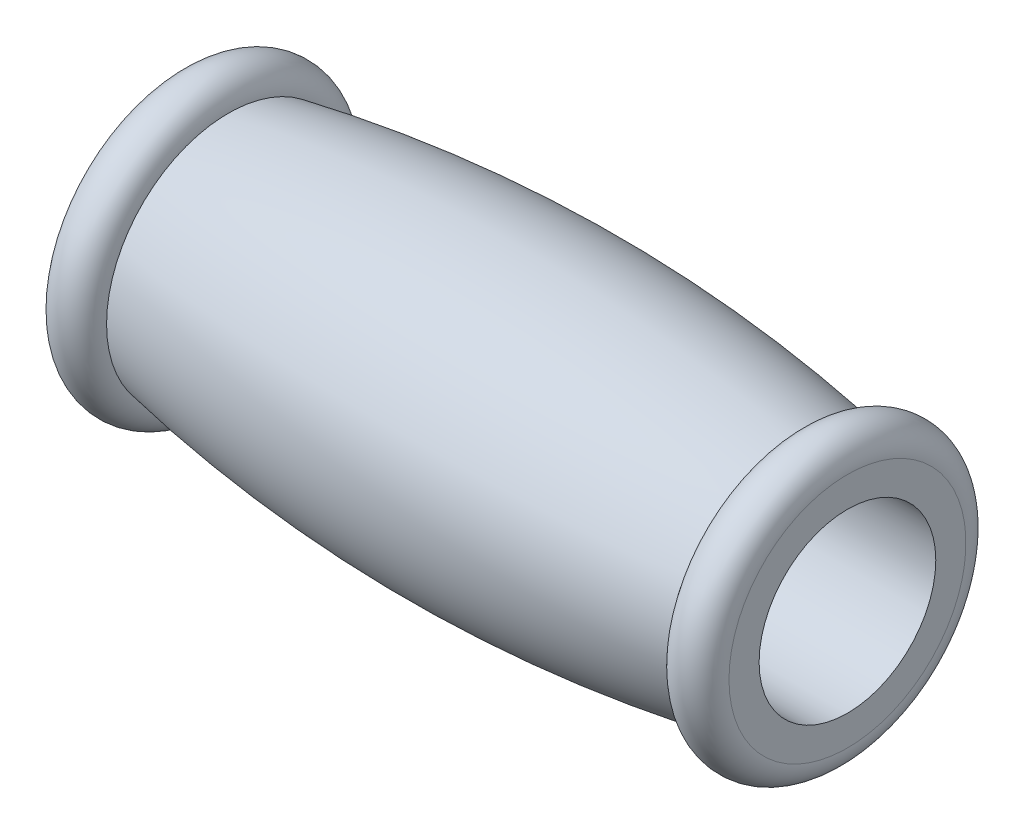
SolidWorks part; units mm, degrees
ref_plane "Front Plane" through (0, 0, 0) normal (0, 0, 1) x (1, 0, 0)
ref_plane "Top Plane" through (0, 0, 0) normal (0, 1, 0) x (1, 0, 0)
ref_plane "Right Plane" through (0, 0, 0) normal (1, 0, 0) x (0, 0, -1)
sketch "Sketch1" plane through (0, 0, 0) normal (0, 0, 1) x (1, 0, 0)
  line L0 (-100, 0) -> (119.2913, 0) construction
  line L1 (-50, 13.2) -> (50, 13.2)
  line L2 (0, 0) -> (0, 13.2) construction
  line L4 (-50, 13.2) -> (-50, 18.2)
  line L7 (50, 13.2) -> (50, 17.7)
  arc A0 (-42.5, 18.2) -> (-50, 18.2) centre (-46.25, 18.2) ccw
  arc A1 (-42.5, 18.2) -> (42.5, 18.2) centre (0, -207.2528) cw
  arc A2 (50, 17.7) -> (42.5, 18.2) centre (46.25, 17.95) ccw
  point P5 (0, 13.2)
  point P11 (0, 17.7)
  dimension "D1" = 100
  dimension "D2" = 85
  dimension "D4" = 13.2
revolve "Revolve1" add sketch "Sketch1" angle 360 about L0
